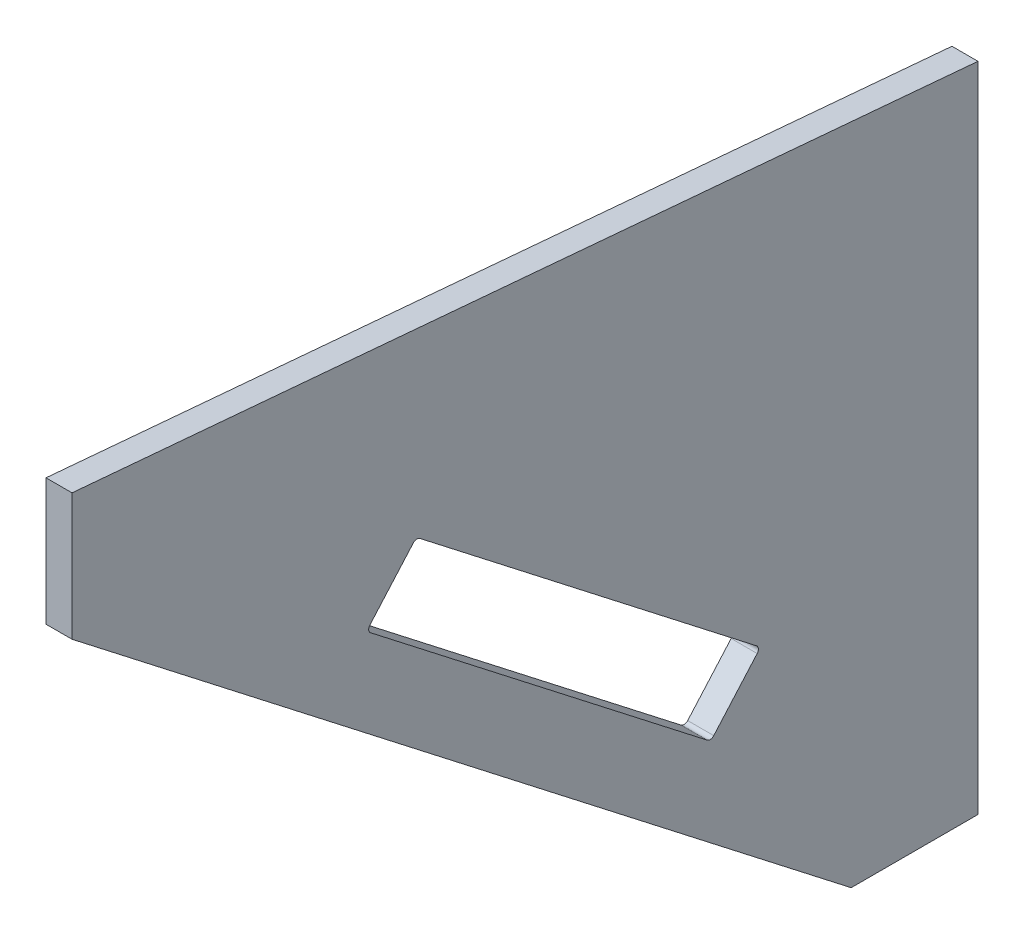
SolidWorks part; units mm, degrees
material "Pine"
ref_plane "Front Plane" through (0, 0, 0) normal (0, 0, 1) x (1, 0, 0)
ref_plane "Top Plane" through (0, 0, 0) normal (0, 1, 0) x (1, 0, 0)
ref_plane "Right Plane" through (0, 0, 0) normal (1, 0, 0) x (0, 0, -1)
sketch "Sketch1" plane through (0, 0, 0) normal (1, 0, 0) x (0, 0, -1)
  line L0 (0, 0) -> (-635, 55.5553)
  line L1 (-635, 55.5553) -> (-635, -33.3375)
  line L2 (-635, -33.3375) -> (-88.9, -457.2)
  line L3 (-88.9, -457.2) -> (0, -457.2)
  line L4 (0, -457.2) -> (0, 0)
  line L5 (-635, -33.3375) -> (-88.9, -81.1151) construction
  line L6 (-88.9, -81.1151) -> (-88.9, -457.2) construction
  dimension "D1" = 88.9
  dimension "D2" = 423.8625
  dimension "D3" = 635
  dimension "D4" = 457.2
  dimension "D5" = 95
  dimension "D6" = 512.7553
extrude "Boss-Extrude1" add sketch "Sketch1" along normal blind 18.2562
sketch "Sketch2" plane through (18.2562, 0, 0) normal (1, 0, 0) x (0, 0, -1)
  line L0 (0, -44.273) -> (-218.2414, -25.1794) construction
  line L1 (-218.2414, -25.1794) -> (-610.4432, 9.1339) construction
  line L2 (0, -88.8928) -> (-635, -33.3375) construction
  line L3 (0, -457.2) -> (0, 0) construction
  line L4 (0, 0) -> (-635, 55.5553) construction
  line L5 (-88.9, -457.2) -> (-88.9, -81.1151) construction
  line L6 (-44.45, -457.2) -> (-44.45, -126.9928) construction
  line L7 (-88.9, -457.2) -> (0, -457.2) construction
  point P17 (-44.45, -431.7928)
  dimension "D1" = 44.45
  dimension "D2" = 219.075
  dimension "D3" = 393.7
  dimension "D4" = 38.1
  dimension "D5" = 304.8
sketch "Sketch3" plane through (0, 0, 0) normal (-1, 0, 0) x (0, 0, 1)
  line L0 (88.9, -457.2) -> (0, -457.2) construction
  line L2 (428.625, -131.7625) -> (187.325, -319.0875)
  line L3 (393.7, -92.075) -> (152.4, -279.4)
  line L4 (152.4, -279.4) -> (187.325, -319.0875)
  line L5 (393.7, -92.075) -> (428.625, -131.7625)
  line L6 (0, -457.2) -> (0, 0) construction
  point P0 (428.3301, -131.7625)
  dimension "D1" = 138.1125
  dimension "D2" = 177.8
  dimension "D3" = 365.125
  dimension "D4" = 325.4375
  dimension "D5" = 152.4
  dimension "D6" = 187.325
  dimension "D7" = 393.7
  dimension "D8" = 428.625
extrude "Cut-Extrude1" cut sketch "Sketch3" against normal through all
fillet "Fillet1" radius 3.3782 4 edges at (9.1281, -92.075, 393.7) (9.1281, -131.7625, 428.625) (9.1281, -279.4, 152.4) (9.1281, -319.0875, 187.325)
